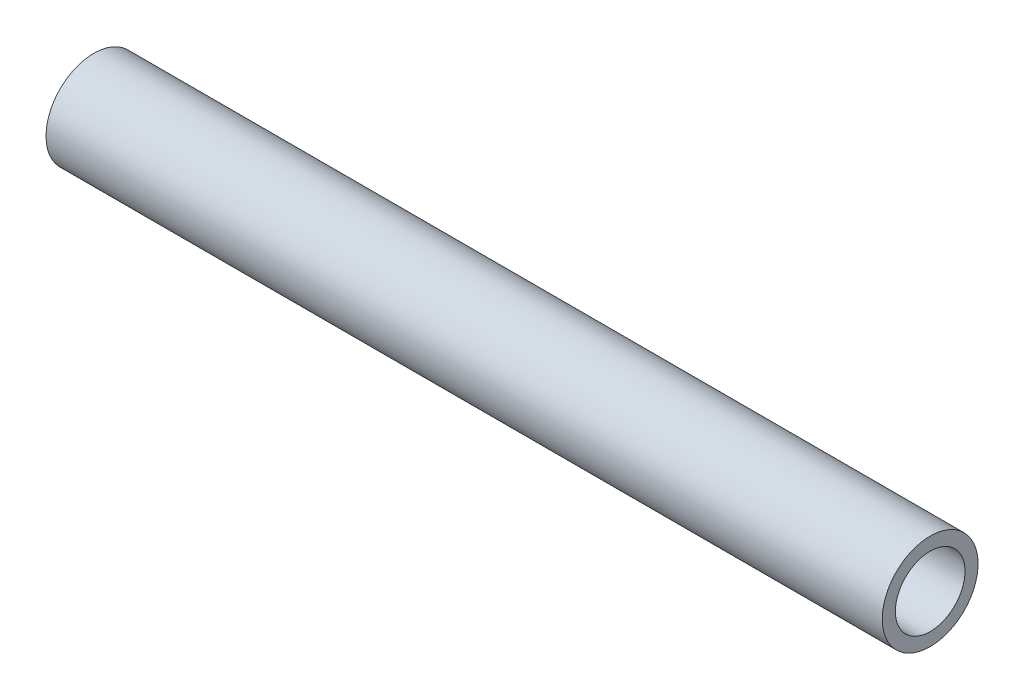
SolidWorks part; units mm, degrees
ref_plane "Front" through (0, 0, 0) normal (0, 0, 1) x (1, 0, 0)
ref_plane "Top" through (0, 0, 0) normal (0, 1, 0) x (1, 0, 0)
ref_plane "Right" through (0, 0, 0) normal (1, 0, 0) x (0, 0, -1)
sketch "Sketch1" plane through (0, 0, 0) normal (1, 0, 0) x (0, 0, -1)
  circle A0 centre (0, 0) radius 17.4625
  circle A1 centre (0, 0) radius 12.7
  point P4 (17.4625, 0)
  point P5 (12.7, 0)
  dimension "OD" = 34.925
  dimension "ID" = 25.4
  dimension "Wall" = 4.7625
extrude "Extrude1" add sketch "Sketch1" along normal mid plane 304.8
